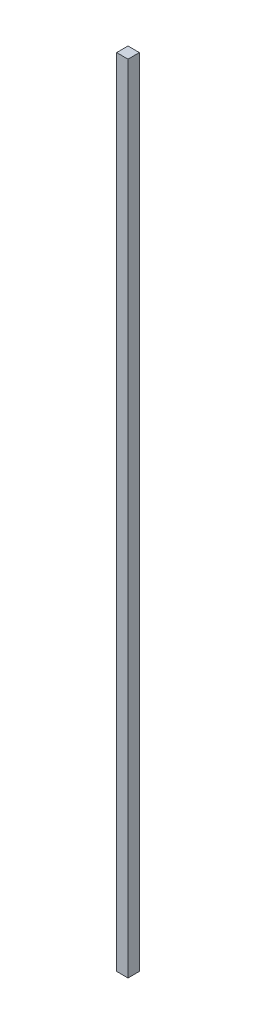
SolidWorks part; units mm, degrees
material "Hexcel AS4C (3000 Filaments)"
ref_plane "Front Plane" through (0, 0, 0) normal (0, 0, 1) x (1, 0, 0)
ref_plane "Top Plane" through (0, 0, 0) normal (0, 1, 0) x (1, 0, 0)
ref_plane "Right Plane" through (0, 0, 0) normal (1, 0, 0) x (0, 0, -1)
sketch "Sketch1" plane through (0, 0, 0) normal (0, 1, 0) x (1, 0, 0)
  line L1 (3, 3) -> (-3, 3)
  line L2 (3, 3) -> (3, -3)
  line L3 (3, -3) -> (-3, -3)
  line L4 (-3, 3) -> (-3, -3)
  line L5 (3, 3) -> (-3, -3) construction
  line L6 (3, -3) -> (-3, 3) construction
  point P0 (0, 0)
  dimension "D1" = 6
  dimension "D2" = 6
extrude "Boss-Extrude1" add sketch "Sketch1" along normal blind 420
